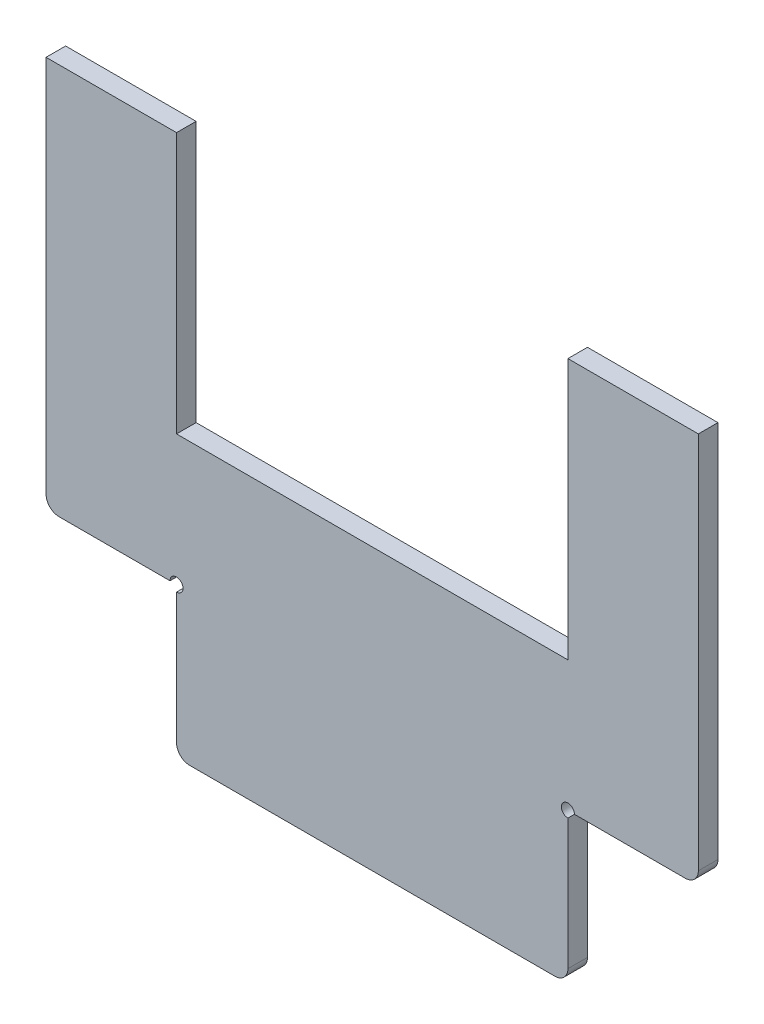
SolidWorks part; units mm, degrees
material "Thornel Mat VMA"
ref_plane "Front Plane" through (0, 0, 0) normal (0, 0, 1) x (1, 0, 0)
ref_plane "Top Plane" through (0, 0, 0) normal (0, 1, 0) x (1, 0, 0)
ref_plane "Right Plane" through (0, 0, 0) normal (1, 0, 0) x (0, 0, -1)
sketch "Sketch1" plane through (0, 0, 0) normal (0, 0, 1) x (1, 0, 0)
  line L0 (0, 11.5) -> (0, 0) construction
  line L1 (-30, -11.5) -> (30, -11.5)
  line L2 (-30, -11.5) -> (-30, 11.5)
  line L3 (-30, 11.5) -> (30, 11.5)
  line L4 (30, -11.5) -> (30, 11.5)
  line L5 (-30, -11.5) -> (30, 11.5) construction
  line L6 (-30, 11.5) -> (30, -11.5) construction
  point P0 (0, 0)
  dimension "D1" = 23
  dimension "D2" = 60
extrude "Boss-Extrude1" add sketch "Sketch1" along normal blind 3
sketch "Sketch2" plane through (0, 0, 3) normal (0, 0, 1) x (1, 0, 0)
  line L0 (0, 11.5) -> (0, 0) construction
  line L1 (30, 11.5) -> (-30, 11.5) construction
  line L3 (50, 11.5) -> (-50, 11.5)
  line L4 (0, 11.5) -> (0, 31.5) construction
  line L5 (30, 31.5) -> (-30, 31.5)
  line L8 (-50, 11.5) -> (-50, 71.5)
  line L9 (-50, 71.5) -> (-30, 71.5)
  line L10 (-30, 31.5) -> (-30, 71.5)
  line L11 (30, 31.5) -> (30, 71.5)
  line L12 (50, 71.5) -> (30, 71.5)
  line L13 (50, 11.5) -> (50, 71.5)
  dimension "D1" = 50
  dimension "D2" = 20
  dimension "D3" = 60
  dimension "D4" = 20
extrude "Boss-Extrude2" add sketch "Sketch2" against normal up to surface (3 mm away) up to face at (0, 0, 0)
sketch "Sketch3" plane through (0, 0, 3) normal (0, 0, 1) x (1, 0, 0)
  circle A0 centre (-30, 11.5) radius 1
  circle A1 centre (30, 11.5) radius 1
  dimension "D1" = 2
extrude "Cut-Extrude1" cut sketch "Sketch3" against normal through all
fillet "Fillet1" radius 2 4 edges at (50, 11.5, 1.5) (-50, 11.5, 1.5) (30, -11.5, 1.5) (-30, -11.5, 1.5)
